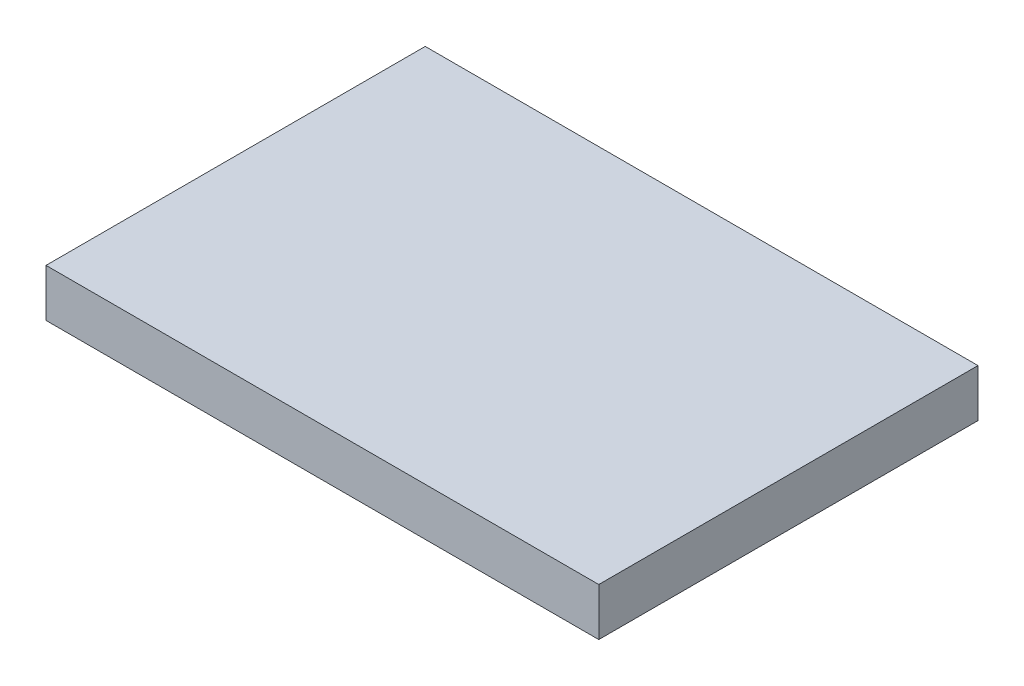
SolidWorks part; units mm, degrees
ref_plane "Front Plane" through (0, 0, 0) normal (0, 0, 1) x (1, 0, 0)
ref_plane "Top Plane" through (0, 0, 0) normal (0, 1, 0) x (1, 0, 0)
ref_plane "Right Plane" through (0, 0, 0) normal (1, 0, 0) x (0, 0, -1)
sketch "Sketch6" plane through (0, 0, 0) normal (0, 1, 0) x (1, 0, 0)
  line L1 (0, 0) -> (147.1919, 0)
  line L2 (0, 0) -> (0, 100.9795)
  line L3 (0, 100.9795) -> (147.1919, 100.9795)
  line L4 (147.1919, 0) -> (147.1919, 100.9795)
extrude "Extrude1" add sketch "Sketch6" along normal blind 12.7
ref_plane "Plane3" through (0, 25.4, 0) normal (0, 1, 0) x (-1, 0, 0)
sketch "Sketch8" plane through (0, 25.4, 0) normal (0, 1, 0) x (-1, 0, 0)
  circle A0 centre (-78.1336, -52.4863) radius 19.0581
